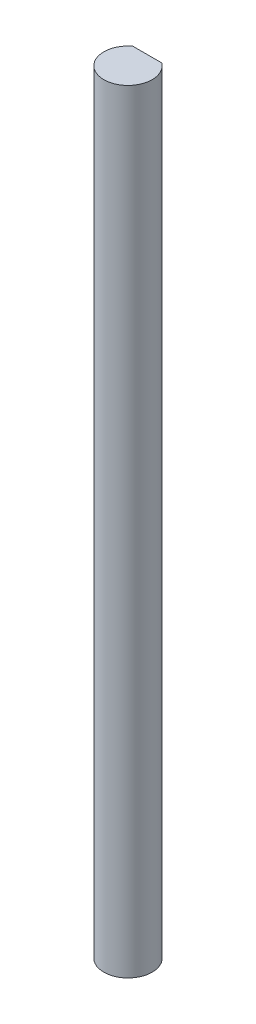
SolidWorks part; units mm, degrees
ref_plane "Front Plane" through (0, 0, 0) normal (0, 0, 1) x (1, 0, 0)
ref_plane "Top Plane" through (0, 0, 0) normal (0, 1, 0) x (1, 0, 0)
ref_plane "Right Plane" through (0, 0, 0) normal (1, 0, 0) x (0, 0, -1)
sketch "Sketch1" plane through (0, 0, 0) normal (0, 1, 0) x (1, 0, 0)
  circle A0 centre (0, 0) radius 3.175
  dimension "D1" = 6.35
extrude "Boss-Extrude1" add sketch "Sketch1" along normal blind 101.6
sketch "Sketch2" plane through (0, 0, 0) normal (0, -1, 0) x (1, 0, 0)
  line L0 (1.905, -2.54) -> (-1.905, -2.54)
  line L1 (0, 0) -> (0, -2.54) construction
  circle A0 centre (0, 0) radius 3.175 construction
  arc A1 (-1.905, -2.54) -> (1.905, -2.54) centre (0, 0) ccw
  dimension "D1" = 5.715
extrude "Cut-Extrude1" cut sketch "Sketch2" against normal through all
